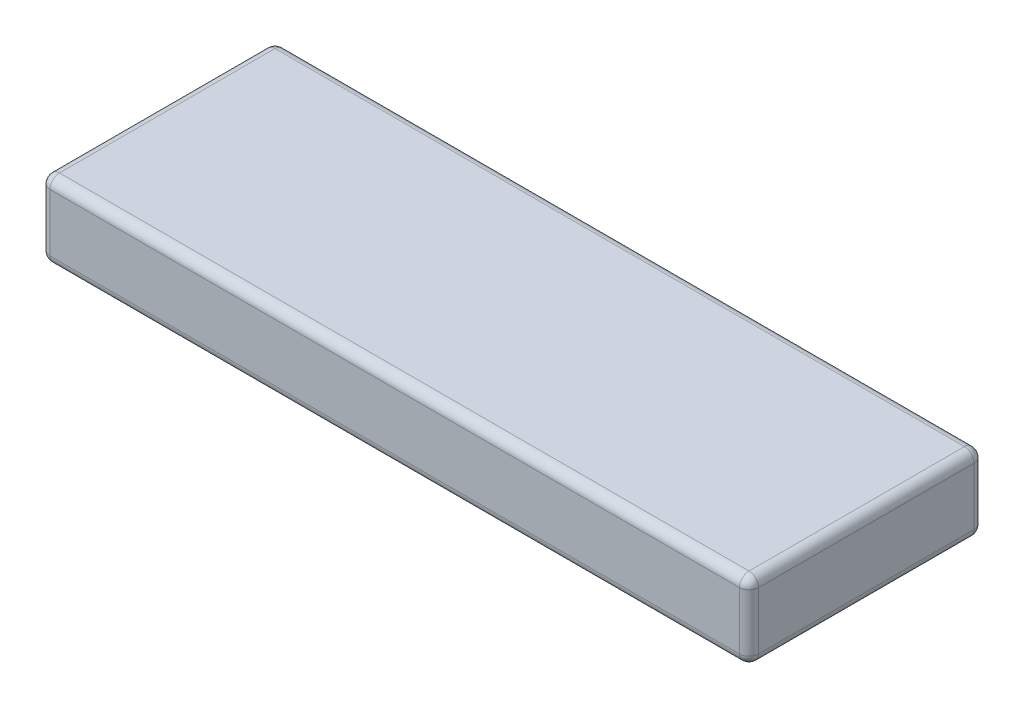
SolidWorks part; units mm, degrees
ref_plane "Front Plane" through (0, 0, 0) normal (0, 0, 1) x (1, 0, 0)
ref_plane "Top Plane" through (0, 0, 0) normal (0, 1, 0) x (1, 0, 0)
ref_plane "Right Plane" through (0, 0, 0) normal (1, 0, 0) x (0, 0, -1)
sketch "Sketch1" plane through (0, 0, 0) normal (0, 1, 0) x (1, 0, 0)
  line L0 (-85.9648, 0) -> (62.0352, 0)
  line L1 (62.0352, 0) -> (62.0352, 49)
  line L2 (62.0352, 49) -> (-85.9648, 49)
  line L3 (-85.9648, 49) -> (-85.9648, 0)
  dimension "D1" = 148
  dimension "D2" = 49
extrude "Boss-Extrude1" add sketch "Sketch1" along normal blind 16
fillet "Fillet1" radius 2 12 edges at (-11.9648, 0, 0) (-85.9648, 8, 0) (-85.9648, 0, -24.5) (-85.9648, 8, -49) (-11.9648, 0, -49) (62.0352, 8, -49) (62.0352, 0, -24.5) (62.0352, 8, 0) (62.0352, 16, -24.5) (-11.9648, 16, -49) (-85.9648, 16, -24.5) (-11.9648, 16, 0)
